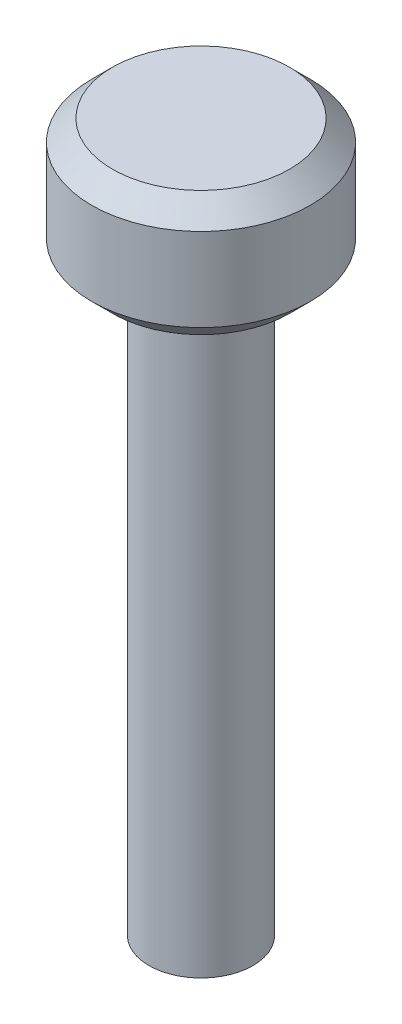
SolidWorks part; units mm, degrees
ref_plane "Alzado" through (0, 0, 0) normal (0, 0, 1) x (1, 0, 0)
ref_plane "Planta" through (0, 0, 0) normal (0, 1, 0) x (1, 0, 0)
ref_plane "Vista lateral" through (0, 0, 0) normal (1, 0, 0) x (0, 0, -1)
sketch "Sketch2" plane through (0, 0, 0) normal (0, 0, 1) x (1, 0, 0)
  line L0 (0, 0.2957) -> (0, 34) construction
  line L1 (0, 34) -> (-4.25, 34)
  line L2 (-5.25, 33) -> (-5.25, 29)
  line L3 (-4.25, 28) -> (-2.5, 28)
  line L4 (-2.5, 28) -> (-2.5, 0)
  line L5 (-2.5, 0) -> (0, 0) construction
  line L7 (-5.25, 33) -> (-4.25, 34)
  line L8 (0, 34) -> (0, 0.2957)
  line L11 (-5.25, 29) -> (-4.25, 28)
  line L12 (-2.5, 0) -> (0, 0.2957)
  line L13 (0, 0.2957) -> (0, 0) construction
  dimension "D1" = 10.5
  dimension "D2" = 1
  dimension "D3" = 34
  dimension "D4" = 5
  dimension "D5" = 1
  dimension "D6" = 1
  dimension "D7" = 6
  dimension "D8" = 0.2957
revolve "Revolve1" add sketch "Sketch2" angle 360 about L0
